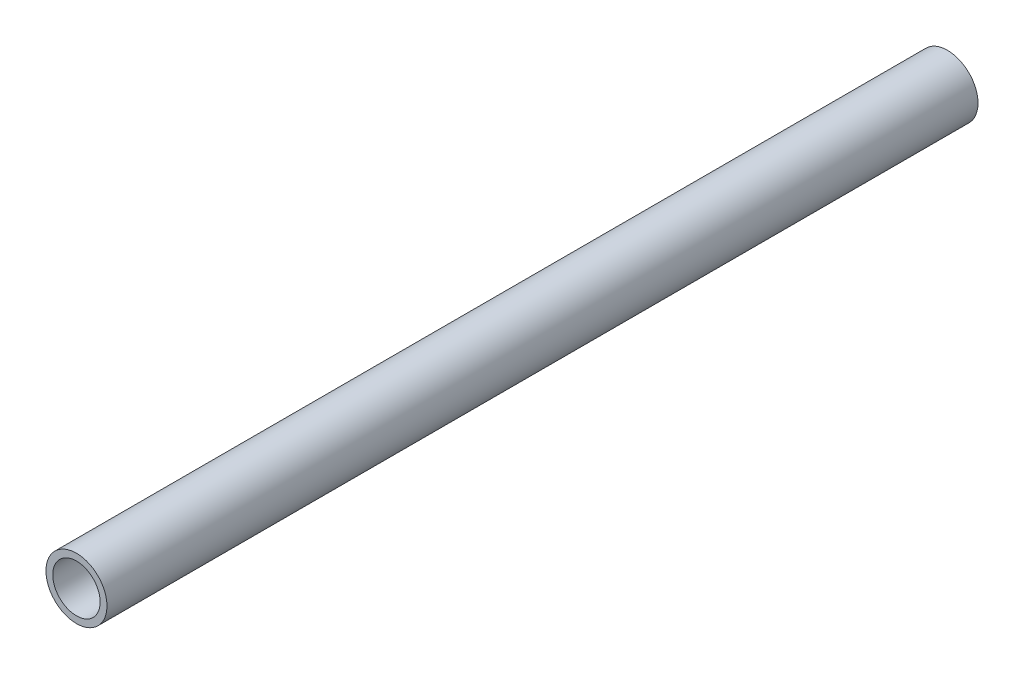
SolidWorks part; units mm, degrees
ref_plane "Front Plane" through (0, 0, 0) normal (0, 0, 1) x (1, 0, 0)
ref_plane "Top Plane" through (0, 0, 0) normal (0, 1, 0) x (1, 0, 0)
ref_plane "Right Plane" through (0, 0, 0) normal (1, 0, 0) x (0, 0, -1)
sketch "Sketch1" plane through (0, 0, 0) normal (0, 0, 1) x (1, 0, 0)
  circle A0 centre (0, 0) radius 7
  circle A1 centre (0, 0) radius 9
  dimension "D1" = 14
  dimension "D2" = 18
extrude "Boss-Extrude1" add sketch "Sketch1" along normal blind 257
